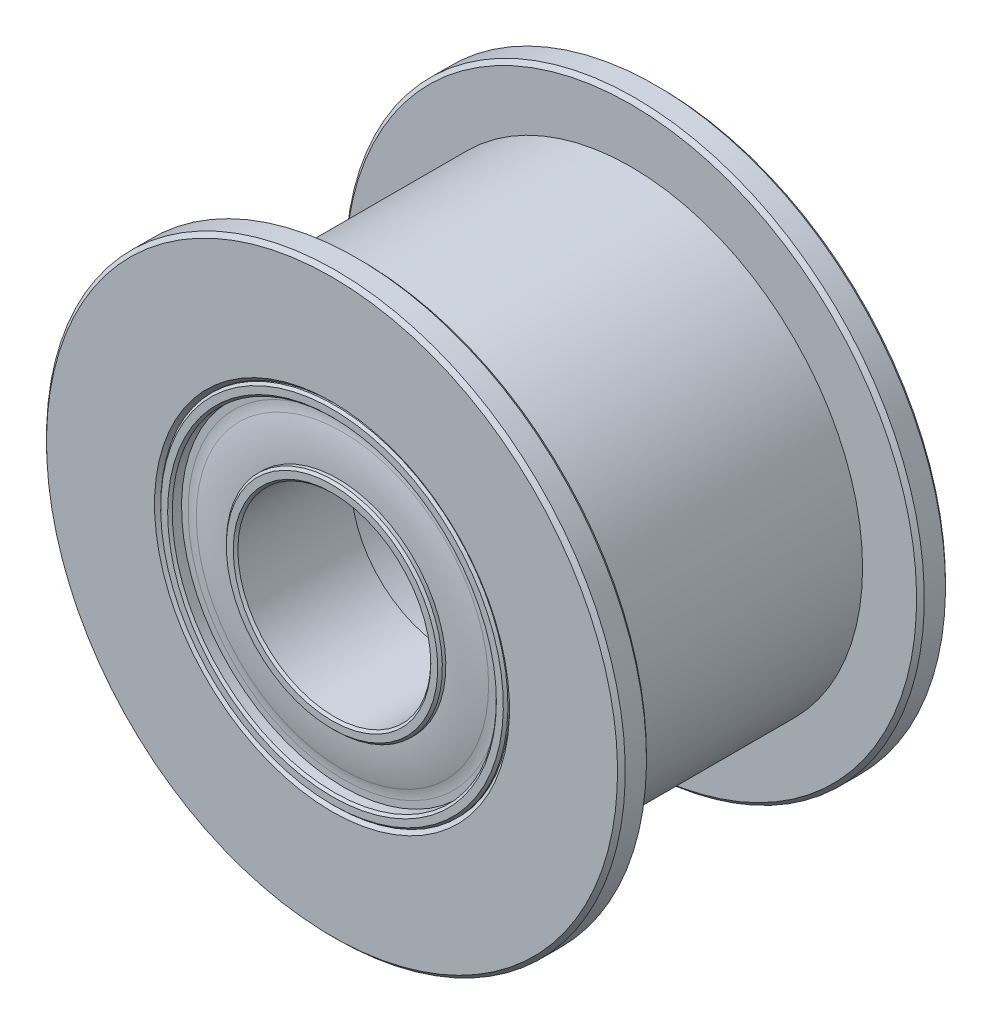
SolidWorks part; units mm, degrees
ref_plane "Front" through (0, 0, 0) normal (0, 0, 1) x (1, 0, 0)
ref_plane "Top" through (0, 0, 0) normal (0, 1, 0) x (1, 0, 0)
ref_plane "Right" through (0, 0, 0) normal (1, 0, 0) x (0, 0, -1)
sketch "Sketch1" plane through (0, 0, 0) normal (1, 0, 0) x (0, 0, -1)
  line L0 (-4.25, 0) -> (4.25, 0) construction
  line L1 (4.25, 7.5) -> (4.25, -7.5) construction
  line L2 (4.25, 7.5) -> (3.5, 7.5) construction
  line L3 (4.25, 2.5) -> (4.25, -2.5) construction
  line L4 (4.25, 6) -> (4.25, -6) construction
  line L5 (3, 0) -> (-3, 0) construction
  line L6 (3.5, 7.5) -> (3.5, 6) construction
  line L7 (4.25, 4.5) -> (1.25, 4.5) construction
  line L8 (1.25, 4.5) -> (1.25, 2.5) construction
  line L9 (1.25, 2.5) -> (4.25, 2.5) construction
  line L10 (4.25, 4.5) -> (4.25, -4.5) construction
  line L11 (-4.25, 0) -> (-4.25, 7.5) construction
  line L12 (-4.25, 7.5) -> (-3.5, 7.5) construction
  line L13 (-3.5, 7.5) -> (-3.5, 6) construction
  line L14 (-3.5, 6) -> (3.5, 6) construction
  line L15 (3.5, 6) -> (3.5, -6) construction
  line L16 (3.5, -6) -> (-3.5, -6) construction
  line L17 (-3.5, -6) -> (-3.5, 6) construction
  line L18 (0, -3.5) -> (0, 3.5) construction
  point P15 (4.25, 0)
  point P22 (3.5, 0)
  point P24 (-3, -6)
  point P25 (3, -6)
  point P29 (0, 0)
  dimension "Width" = 8.5
  dimension "OD" = 15
  dimension "ID" = 5
  dimension "Diameter" = 12
  dimension "Groove Depth" = 1.5
  dimension "For Maximum Belt Width" = 6
  dimension "For Shaft Diameter" = 5
  dimension "Bearing Diameter" = 9
  dimension "Bearing Width" = 3
  dimension "Inside Width" = 7
  dimension "Wall Thickness" = 0.75
  dimension "D1" = 7
sketch "Sketch5" plane through (0, 0, 0) normal (0, 0, 1) x (1, 0, 0)
  circle A0 centre (0, 0) radius 7.5 construction
  circle A1 centre (0, 0) radius 6 construction
  circle A2 centre (0, 0) radius 2.5 construction
  point P5 (0, 0)
  point P9 (-6, 0)
  point P10 (-7.5, 0)
  point P13 (0, 6)
sketch "Sketch2" plane through (0, 0, 0) normal (1, 0, 0) x (0, 0, -1)
  line L0 (4.25, 2.5) -> (1.25, 2.5)
  line L1 (4.25, 2.5) -> (4.25, 2.8)
  line L2 (4.25, 7.5) -> (4.25, -7.5) construction
  line L3 (4.25, 2.8) -> (3.95, 2.8) construction
  line L4 (4.1, 4.2) -> (4.1, 2.8) construction
  line L5 (4.25, 4.5) -> (1.25, 4.5)
  line L6 (3.95, 3.9) -> (3.95, 4.2)
  line L7 (4.25, 4.5) -> (4.25, 4.2)
  line L8 (4.25, 4.2) -> (3.95, 4.2)
  line L9 (3.95, 4.2) -> (3.95, 2.8) construction
  line L10 (1.25, 4.5) -> (1.25, 2.5)
  line L11 (4.1, 2.8) -> (4.25, 2.8)
  arc A0 (3.95, 3.9) -> (4.1, 2.8) centre (-0.0083, 2.8) cw
  dimension "D1" = 0.3
revolve "Revolve1" add sketch "Sketch2" angle 360 about L0
chamfer "Chamfer2" distance 0.06 angle 45 4 edges at (0, -2.8, -4.25) (0, -2.5, -4.25) (0, -4.2, -4.25) (0, -4.5, -4.25)
fillet "Fillet2" radius 1 1 edges at (0, -3.9, -3.95)
mirror "Mirror1" about plane through (0, 0, 0) normal (0, 0, 1) of bodies 108
sketch "Sketch3" plane through (0, 0, 0) normal (1, 0, 0) x (0, 0, -1)
  line L0 (3.5, 7.5) -> (4.25, 7.5)
  line L1 (4.25, 7.5) -> (4.25, 4.5)
  line L2 (4.25, 7.5) -> (4.25, -7.5) construction
  line L3 (-4.25, 4.5) -> (-1.25, 4.5)
  line L4 (-1.25, 4.5) -> (-1.25, 3.5)
  line L5 (-1.25, 3.5) -> (1.25, 3.5)
  line L6 (1.25, 3.5) -> (1.25, 4.5)
  line L8 (1.25, 4.5) -> (4.25, 4.5)
  line L9 (3.5, 7.5) -> (3.5, 6)
  line L10 (3.5, 6) -> (-3.5, 6)
  line L11 (0, 6) -> (0, 4.5) construction
  line L12 (-4.25, 4.5) -> (4.25, 4.5) construction
  line L13 (-3.5, 7.5) -> (-3.5, 6)
  line L19 (-4.25, 7.5) -> (-4.25, 4.5)
  line L20 (-3.5, 7.5) -> (-4.25, 7.5)
revolve "Revolve2" add sketch "Sketch3" angle 360 about L0
chamfer "Chamfer1" distance 0.1 angle 45 6 edges at (0, -7.5, -4.25) (0, -7.5, -3.5) (0, -7.5, 3.5) (0, -7.5, 4.25) (0, -4.5, -4.25) (0, -4.5, 4.25)
equation "\"D1@Sketch1\"=\"ID@Sketch1\"+2"
